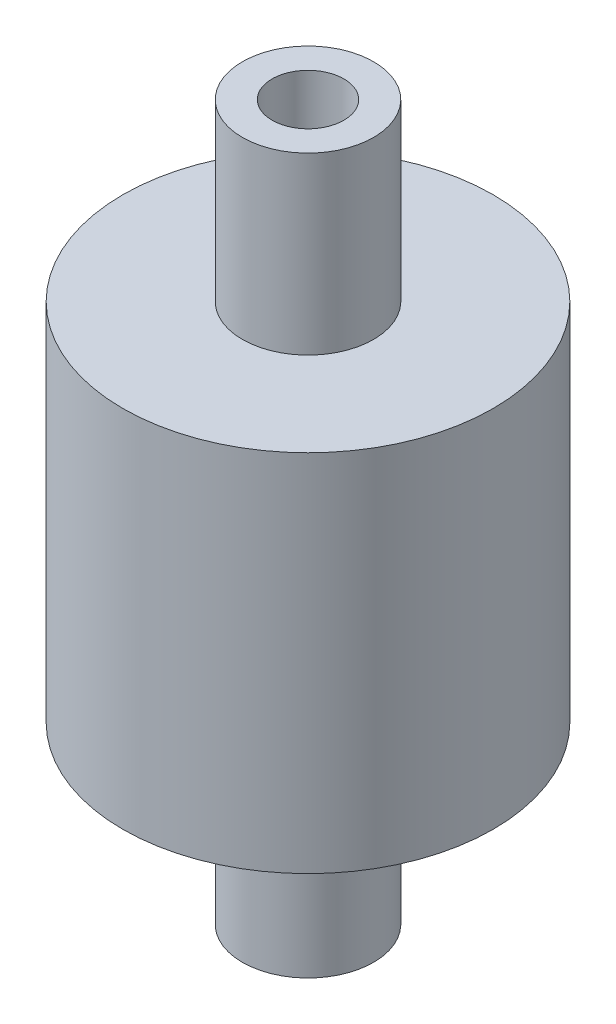
SolidWorks part; units mm, degrees
ref_plane "Alzado" through (0, 0, 0) normal (0, 0, 1) x (1, 0, 0)
ref_plane "Planta" through (0, 0, 0) normal (0, 1, 0) x (1, 0, 0)
ref_plane "Vista lateral" through (0, 0, 0) normal (1, 0, 0) x (0, 0, -1)
sketch "Croquis1" plane through (0, 0, 0) normal (0, 1, 0) x (1, 0, 0)
  circle A0 centre (0, 0) radius 12.7
  dimension "D1" = 25.4
extrude "Saliente-Extruir1" add sketch "Croquis1" along normal mid plane 25
sketch "Croquis2" plane through (0, 0, 0) normal (0, 1, 0) x (1, 0, 0)
  circle A0 centre (0, 0) radius 4.5
  dimension "D1" = 9
extrude "Saliente-Extruir2" add sketch "Croquis2" along normal mid plane 49
sketch "Croquis3" plane through (0, 0, 0) normal (0, 1, 0) x (1, 0, 0)
  circle A0 centre (0, 0) radius 2.4607
extrude "Cortar-Extruir1" cut sketch "Croquis3" against normal through all both and the other way through all
